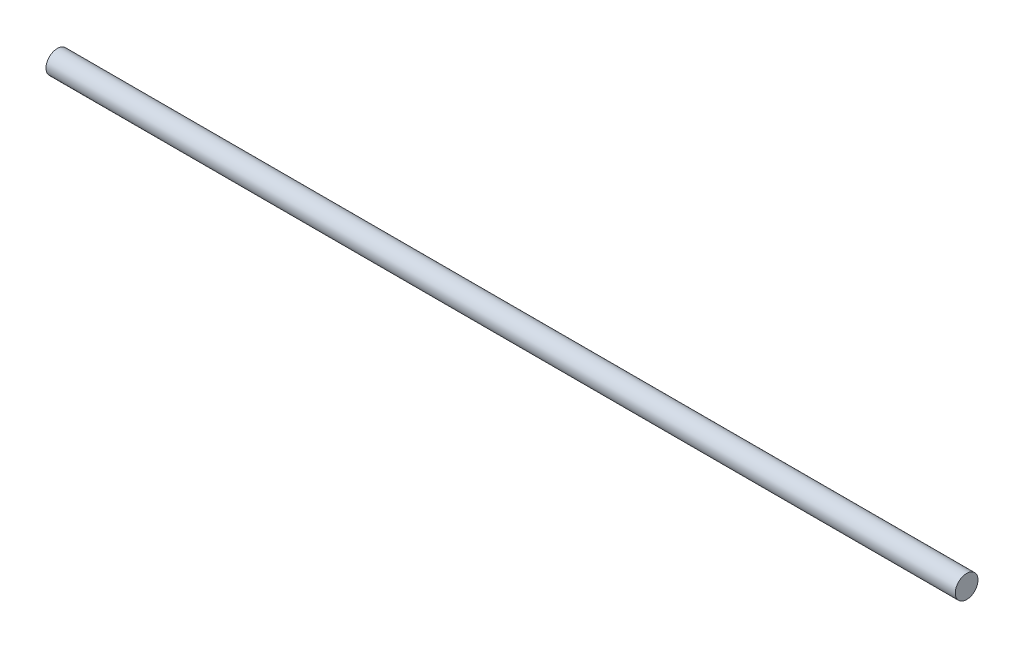
SolidWorks part; units mm, degrees
ref_plane "정면" through (0, 0, 0) normal (0, 0, 1) x (1, 0, 0)
ref_plane "윗면" through (0, 0, 0) normal (0, 1, 0) x (1, 0, 0)
ref_plane "우측면" through (0, 0, 0) normal (1, 0, 0) x (0, 0, -1)
sketch "스케치1" plane through (0, 0, 0) normal (1, 0, 0) x (0, 0, -1)
  circle A0 centre (0, 0) radius 1.25
  dimension "D1" = 2.5
extrude "보스-돌출1" add sketch "스케치1" along normal mid plane 100
